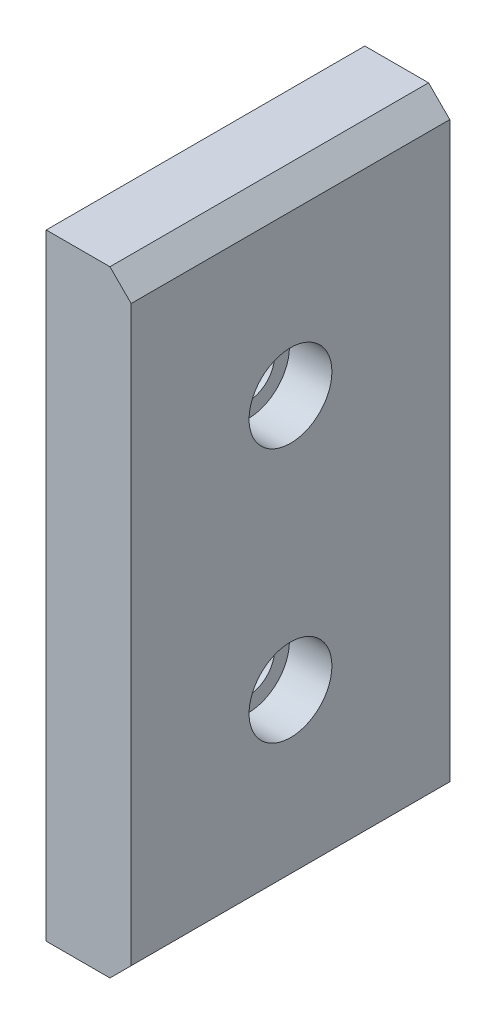
SolidWorks part; units mm, degrees
ref_plane "Спереди" through (0, 0, 0) normal (0, 0, 1) x (1, 0, 0)
ref_plane "Сверху" through (0, 0, 0) normal (0, 1, 0) x (1, 0, 0)
ref_plane "Справа" through (0, 0, 0) normal (1, 0, 0) x (0, 0, -1)
sketch "Эскиз1" plane through (0, 0, 0) normal (1, 0, 0) x (0, 0, -1)
  line L0 (-7.5, 0) -> (7.5, 0) construction
  line L1 (-7.5, 14.5) -> (7.5, 14.5)
  line L2 (-7.5, 14.5) -> (-7.5, -14.5)
  line L3 (-7.5, -14.5) -> (7.5, -14.5)
  line L4 (7.5, 14.5) -> (7.5, -14.5)
  line L5 (-7.5, 14.5) -> (7.5, -14.5) construction
  line L6 (-7.5, -14.5) -> (7.5, 14.5) construction
  circle A0 centre (0, 6) radius 1.25
  circle A1 centre (0, -6) radius 1.25
  point P0 (0, 0)
  dimension "D4" = 2.5
  dimension "D1" = 29
  dimension "D2" = 15
  dimension "D3" = 12
extrude "Бобышка-Вытянуть1" add sketch "Эскиз1" along normal blind 4
sketch "Эскиз2" plane through (4, 0, 0) normal (1, 0, 0) x (0, 0, -1)
  circle A0 centre (0, 6) radius 1.95
  circle A1 centre (0, -6) radius 1.95
  dimension "D1" = 3.9
  dimension "D2" = 3.9
extrude "Вырез-Вытянуть1" cut sketch "Эскиз2" against normal blind 2
chamfer "Фаска1" distance 1 angle 45 2 edges at (4, -14.5, 0) (4, 14.5, 0)
equation "\"motor_diameter\"= 30"
equation "\"mm_diameter\"= IIF ( \"motor_diameter\" < 34 , 41 , \"motor_diameter\" + 8 )"
equation "\"upper_shafts_diameter\"= 5"
equation "\"upper_shats_length\"= 180"
equation "\"upper_bearing_d1\"= 10"
equation "\"upper_bearing_d2\"= 5"
equation "\"upper_bearing_h\"= 15"
equation "\"lower_shafts_diameter\"= 5"
equation "\"lower_shafts_length\"= 180"
equation "\"lower_bearing_d1\"= 10"
equation "\"lower_bearing_d2\"= 5"
equation "\"lower_bearing_h\"= 15"
equation "\"print_offset\"= 0.5"
equation "\"bh_screws_d\"= 2"
equation "\"bh_screws_h\"= 20"
equation "\"bh_screws_hh_d\"= 3.4"
equation "\"bh_screws_hh_h\"= 2"
equation "\"bh_nut_d\"= 3.8"
equation "\"bh_nut_h\"= 2"
equation "\"motor_screws_d\"= 3"
equation "\"motor_screws_h\"= 16"
equation "\"motor_screws_hh_d\"= 5.5"
equation "\"motor_screws_hh_h\"= 3"
equation "\"plate_hole_distance\"= 25.4"
equation "\"plate_screws_d\"= 6.5"
equation "\"shafts_diameter\"= IIF ( \"mm_diameter\" < 42 , 42 + 8 , \"mm_diameter\" + 8 )"
equation "\"central_hole_diameter\"= 8"
equation "\"bh_thikness\"= 4"
equation "\"ends_screws_d\"= 4"
equation "\"ends_screws_h\"= 16"
equation "\"ends_screws_hh_d\"= 6.7"
equation "\"ends_screws_hh_h\"= 4.1"
equation "\"ends_nut_d\"= 6.8"
equation "\"ends_nut_h\"= 3"
equation "\"system_radius\" = ( \"shafts_diameter\" + 12 + \"bh_thikness\" / 2 ) / 2"
equation "\"encoder_distance\"= \"system_radius\" + 4"
equation "\"tape_position\"= \"encoder_distance\" - 2 + 3.9 + 1.7 / 2"
equation "\"D1@Эскиз1\"=\"lower_bearing_h\"+\"bh_thikness\"*2+6"
equation "\"D4@Эскиз1\"=\"bh_screws_d\"+\"print_offset\""
equation "\"D1@Эскиз2\"=\"bh_screws_hh_d\"+\"print_offset\""
equation "\"D2@Эскиз2\"=\"D1@Эскиз2\""
equation "\"D1@Вырез-Вытянуть1\"=\"bh_screws_hh_h\""
